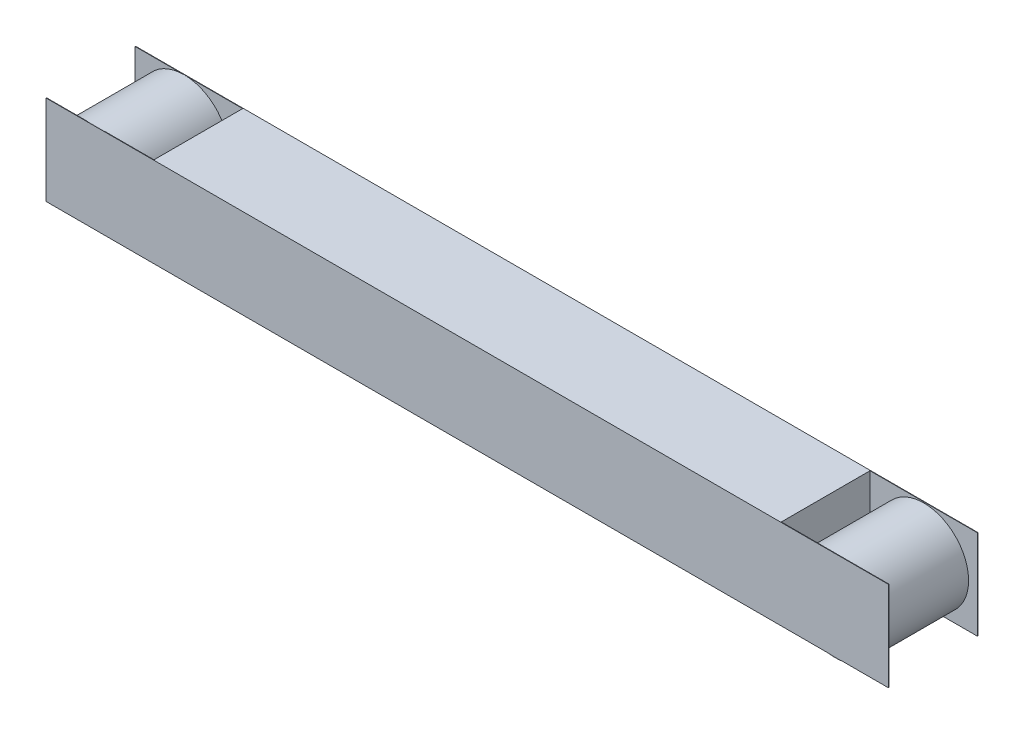
SolidWorks part; units mm, degrees
ref_plane "Front Plane" through (0, 0, 0) normal (0, 0, 1) x (1, 0, 0)
ref_plane "Top Plane" through (0, 0, 0) normal (0, 1, 0) x (1, 0, 0)
ref_plane "Right Plane" through (0, 0, 0) normal (1, 0, 0) x (0, 0, -1)
sketch "Sketch1" plane through (0, 0, 0) normal (0, 0, 1) x (1, 0, 0)
  line L0 (0, 0) -> (47, 0)
  line L1 (47, 0) -> (47, -5)
  line L2 (47, -5) -> (0, -5)
  line L3 (0, -5) -> (0, 0)
  dimension "D1" = 47
  dimension "D2" = 5
extrude "Boss-Extrude1" add sketch "Sketch1" along normal blind 5
ref_plane "Plane1" through (0, 0, 2.5) normal (0, 0, 1) x (1, 0, 0)
sketch "Sketch3" plane through (0, 0, 2.5) normal (0, 0, 1) x (1, 0, 0)
  line L0 (0, 0) -> (0, -5.2641)
  line L1 (0, -5.2641) -> (6, -5.2641)
  line L2 (6, -5.2641) -> (6, 0)
  line L3 (47, 0) -> (0, 0) construction
  line L4 (6, 0) -> (0, 0)
  line L5 (47, 0.1443) -> (47, -5.2641)
  line L6 (47, -5.2641) -> (41, -5.2641)
  line L7 (41, -5.2641) -> (41, 0.1443)
  line L8 (41, 0.1443) -> (47, 0.1443)
  line L9 (47, -5) -> (47, 0) construction
  dimension "D1" = 6
  dimension "D2" = 6
extrude "Cut-Extrude1" cut sketch "Sketch3" against normal mid plane 4.95
sketch "Sketch4" plane through (0, 0, 0.025) normal (0, 0, 1) x (1, 0, 0)
  line L0 (41, 0) -> (41, -5) construction
  circle A0 centre (44, -2.5555) radius 2.5
  dimension "D1" = 5
  dimension "D2" = 3
extrude "Boss-Extrude2" add sketch "Sketch4" along normal blind 4.95
sketch "Sketch5" plane through (0, 0, 0.025) normal (0, 0, 1) x (1, 0, 0)
  line L0 (47, 0) -> (0, 0) construction
  circle A0 centre (2.7317, -2.5) radius 2.5
  dimension "D1" = 5
extrude "Boss-Extrude3" add sketch "Sketch5" along normal blind 4.95
